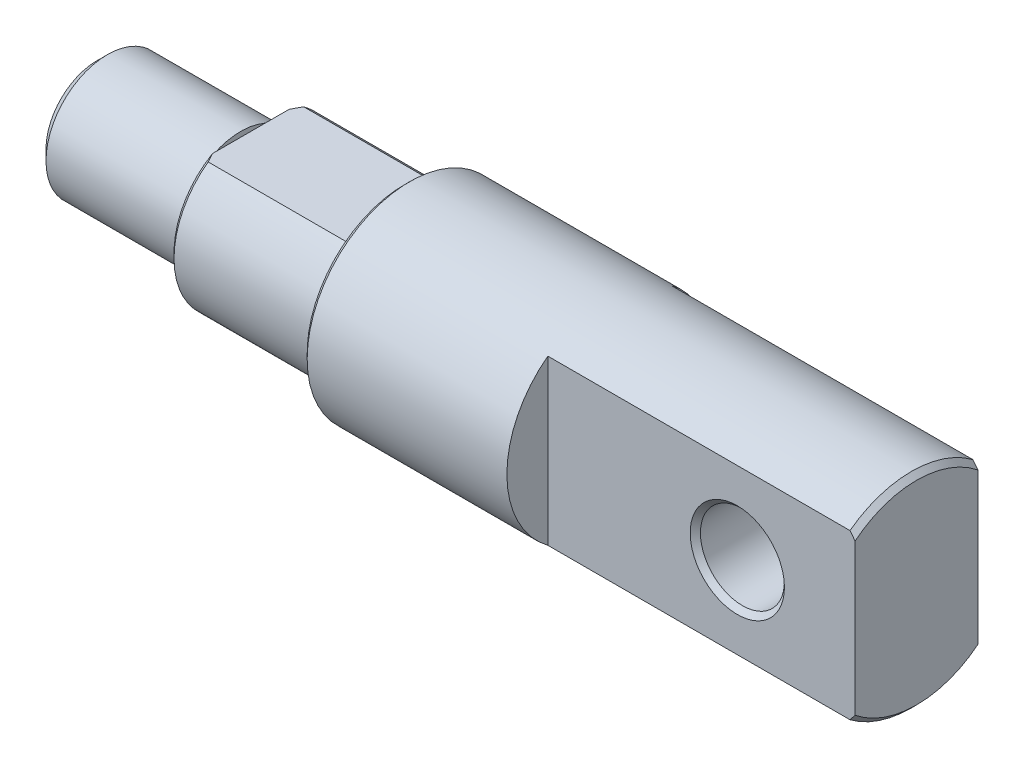
SolidWorks part; units mm, degrees
material "Alliage 6061"
ref_plane "Face" through (0, 0, 0) normal (0, 0, 1) x (1, 0, 0)
ref_plane "Dessus" through (0, 0, 0) normal (0, 1, 0) x (1, 0, 0)
ref_plane "Droite" through (0, 0, 0) normal (1, 0, 0) x (0, 0, -1)
sketch "Esquisse1" plane through (0, 0, 0) normal (0, 0, 1) x (1, 0, 0)
  line L0 (0, 0) -> (54.7909, 0) construction
  line L1 (-50, 8) -> (-65, 8)
  line L2 (-65, 8) -> (-65, 5)
  line L3 (-50, 8) -> (-50, 10)
  line L4 (-50, 10) -> (0, 10)
  line L5 (-66, 6) -> (-80, 6)
  line L6 (-80, 6) -> (-80, 0)
  line L7 (0, 0) -> (-80, 0)
  line L8 (0, 10) -> (0, 0)
  line L9 (-66, 6) -> (-66, 5)
  line L10 (-66, 5) -> (-65, 5)
  dimension "D1" = 15
  dimension "D2" = 15
  dimension "D3" = 16
  dimension "D4" = 12
  dimension "D5" = 5
  dimension "D6" = 20
  dimension "D7" = 50
  dimension "D8" = 1
revolve "Révolution1" add sketch "Esquisse1" angle 360 about L0
cosmetic thread "Représentation de filetage1" parameters "D2"=10.072
chamfer "Chanfrein1" distance 0.5 angle 45 3 edges at (-50, 0, 10) (0, 0, 10) (-65, 0, 8)
chamfer "Chanfrein2" distance 1 angle 45 1 edges at (-80, 0, 6)
sketch "Esquisse2" plane through (0, 0, 0) normal (1, 0, 0) x (0, 0, -1)
  line L1 (-15, 15) -> (-6, 15)
  line L2 (-15, 15) -> (-15, -15)
  line L3 (-15, -15) -> (-6, -15)
  line L4 (-6, 15) -> (-6, -15)
  line L5 (6, 15) -> (15, 15)
  line L6 (6, 15) -> (6, -15)
  line L7 (6, -15) -> (15, -15)
  line L8 (15, 15) -> (15, -15)
  circle A0 centre (0, 0) radius 10 construction
  dimension "D1" = 6
  dimension "D2" = 6
extrude "Enlèv. mat.-Extru.1" cut sketch "Esquisse2" against normal blind 30
sketch "Esquisse3" plane through (0, 0, 6) normal (0, 0, 1) x (1, 0, 0)
  line L0 (-50, 8) -> (-50, -8) construction
  circle A0 centre (-11.5, 0) radius 4.1
  dimension "D1" = 38.5
  dimension "D2" = 8.2
extrude "Enlèv. mat.-Extru.2" cut sketch "Esquisse3" against normal up to next
chamfer "Chanfrein3" distance 0.5 angle 45 2 edges at (-11.5, -4.1, -6) (-7.4, 0, 6)
sketch "Esquisse5" plane through (-50, 0, 0) normal (-1, 0, 0) x (0, 0, 1)
  line L1 (-10, 10) -> (10, 10)
  line L2 (-10, 10) -> (-10, 6.5)
  line L3 (-10, 6.5) -> (10, 6.5)
  line L4 (10, 10) -> (10, 6.5)
  line L5 (-10, -6.5) -> (10, -6.5)
  line L6 (-10, -6.5) -> (-10, -10)
  line L7 (-10, -10) -> (10, -10)
  line L8 (10, -6.5) -> (10, -10)
  circle A1 centre (0, 0) radius 8 construction
  dimension "D1" = 6.5
  dimension "D2" = 6.5
extrude "Enlèv. mat.-Extru.3" cut sketch "Esquisse5" along normal up to next
